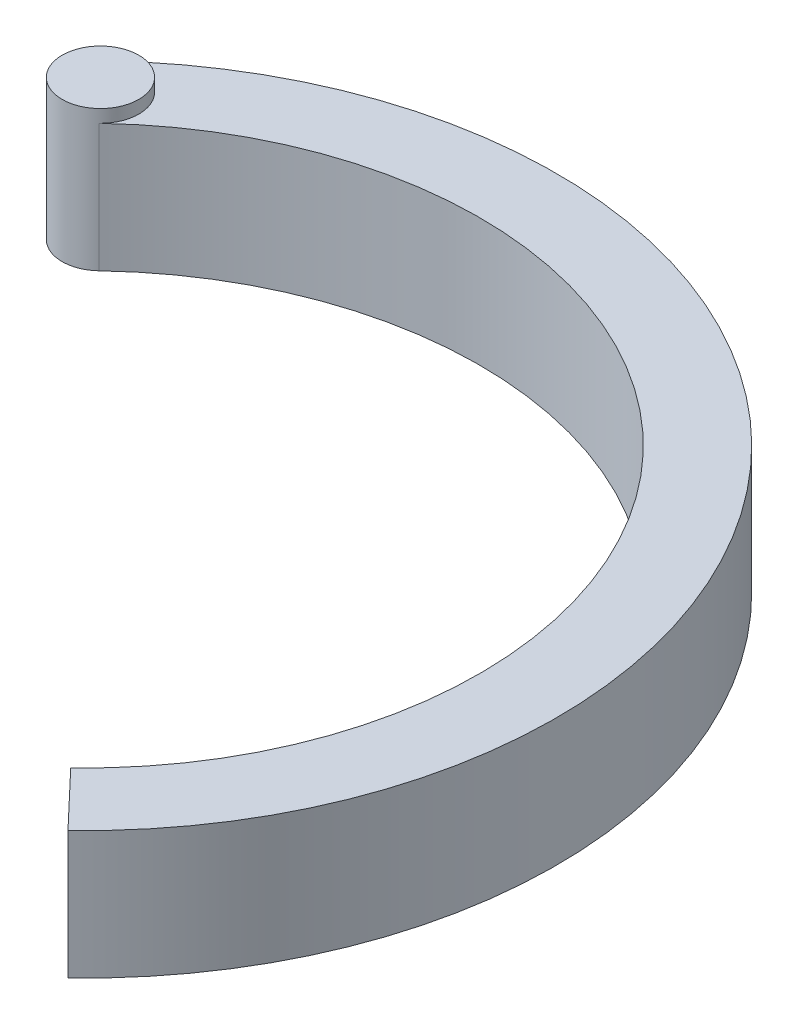
SolidWorks part; units mm, degrees
ref_plane "Front Plane" through (0, 0, 0) normal (0, 0, 1) x (1, 0, 0)
ref_plane "Top Plane" through (0, 0, 0) normal (0, 1, 0) x (1, 0, 0)
ref_plane "Right Plane" through (0, 0, 0) normal (1, 0, 0) x (0, 0, -1)
sketch "Sketch15" plane through (0, 0, 0) normal (0, 1, 0) x (1, 0, 0)
  arc A0 (0, 0) -> (46.7198, -49.1563) centre (23.3599, -24.5781) cw construction
  arc A1 (48.7865, -51.3308) -> (-2.0667, 2.1745) centre (23.3599, -24.5781) ccw
  arc A2 (44.653, -46.9817) -> (2.0667, -2.1745) centre (23.3599, -24.5781) ccw
  arc A3 (44.653, -46.9817) -> (48.7865, -51.3308) centre (46.7198, -49.1563) ccw
  arc A4 (-2.0667, 2.1745) -> (2.0667, -2.1745) centre (0, 0) ccw
  point P3 (47.938, -1.2183)
extrude "Boss-Extrude8" add sketch "Sketch15" along normal blind 10
sketch "Sketch17" plane through (0, 10, 0) normal (0, 1, 0) x (1, 0, 0)
  circle A0 centre (0, 0) radius 3
extrude "Boss-Extrude9" add sketch "Sketch17" along normal blind 1
sketch "Sketch18" plane through (0, 10, 0) normal (0, 1, 0) x (1, 0, 0)
  line L0 (44.653, -46.9817) -> (48.7865, -51.3308)
  arc A0 (48.7865, -51.3308) -> (44.5452, -51.223) centre (46.7198, -49.1563) cw
  arc A1 (44.653, -46.9817) -> (48.7865, -51.3308) centre (46.7198, -49.1563) ccw construction
  arc A2 (44.5452, -51.223) -> (44.653, -46.9817) centre (46.7198, -49.1563) cw
extrude "Cut-Extrude3" cut sketch "Sketch18" against normal blind 52 and the other way blind 48
